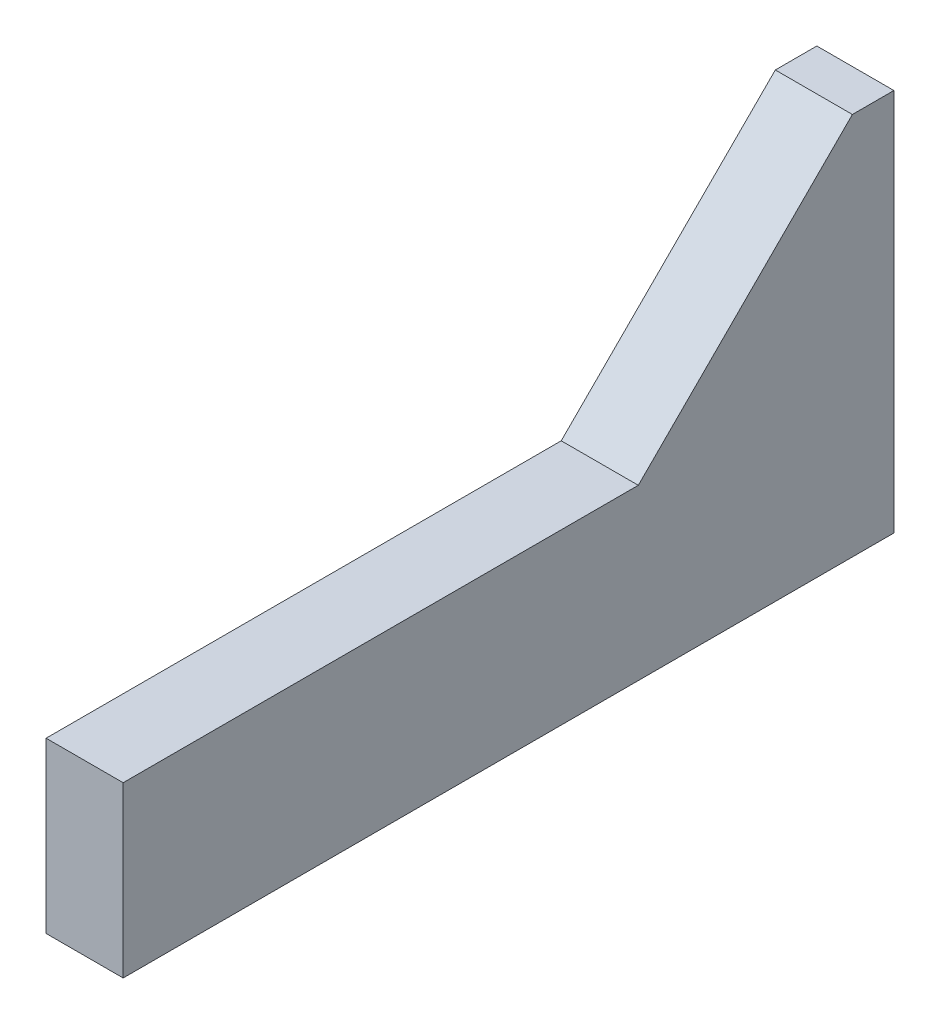
SolidWorks part; units mm, degrees
ref_plane "Спереди" through (0, 0, 0) normal (0, 0, 1) x (1, 0, 0)
ref_plane "Сверху" through (0, 0, 0) normal (0, 1, 0) x (1, 0, 0)
ref_plane "Справа" through (0, 0, 0) normal (1, 0, 0) x (0, 0, -1)
sketch "Эскиз1" plane through (0, 0, 0) normal (0, 0, 1) x (1, 0, 0)
  line L1 (-4.5, -7.5) -> (4.5, -7.5)
  line L2 (-4.5, -7.5) -> (-4.5, 7.5)
  line L3 (-4.5, 7.5) -> (4.5, 7.5)
  line L4 (4.5, -7.5) -> (4.5, 7.5)
  line L5 (-4.5, -7.5) -> (4.5, 7.5) construction
  line L6 (-4.5, 7.5) -> (4.5, -7.5) construction
  line L7 (-4.5, 7.5) -> (4.5, 7.5)
  line L8 (-4.5, 7.5) -> (-4.5, 12.25)
  line L9 (-4.5, 12.25) -> (4.5, 12.25)
  line L10 (4.5, 7.5) -> (4.5, 12.25)
  line L11 (4.5, 7.5) -> (-0.5, 7.5)
  line L12 (4.5, 7.5) -> (4.5, 9.75)
  line L13 (4.5, 9.75) -> (-0.5, 9.75)
  line L14 (-0.5, 7.5) -> (-0.5, 9.75)
  point P0 (0, 0)
  dimension "D1" = 9
  dimension "D2" = 15
  dimension "D3" = 2.25
  dimension "D4" = 2.5
  dimension "D5" = 4
extrude "Бобышка-Вытянуть1" add sketch "Эскиз1" along normal blind 90 contours L1 L4 L7 L3 L2 | L3 L14 L13 L10 L9 L8
sketch "Эскиз2" plane through (0, -7.5, 0) normal (0, -1, 0) x (1, 0, 0)
  line L0 (0, 90) -> (0, 67.5) construction
  line L1 (-4.5, 90) -> (4.5, 90) construction
  line L2 (0, 67.5) -> (0, 45) construction
  line L3 (0, 22.5) -> (0, 0) construction
  line L4 (-4.5, 0) -> (4.5, 0) construction
  line L5 (0, 45) -> (0, 22.5) construction
  circle A0 centre (0, 22.5) radius 2.1
  circle A1 centre (0, 67.5) radius 2.1
  circle A2 centre (0, 45) radius 2.1
  dimension "D1" = 4.2
extrude "Вырез-Вытянуть1" cut sketch "Эскиз2" against normal blind 6
sketch "Эскиз3" plane through (0, 0, 90) normal (0, 0, -1) x (-1, 0, 0)
  line L1 (-4.5, 9.75) -> (0.5, 9.75)
  line L2 (-4.5, 9.75) -> (-4.5, 7.5)
  line L3 (-4.5, 7.5) -> (0.5, 7.5)
  line L4 (0.5, 9.75) -> (0.5, 7.5)
extrude "Бобышка-Вытянуть2" add sketch "Эскиз3" along normal blind 3
chamfer "Фаска1" distance 0.75 angle 45 2 edges at (4.5, 7.5, 43.5) (4.5, 9.75, 43.5)
sketch "Эскиз5" plane through (-4.5, 0, 0) normal (-1, 0, 0) x (0, 0, 1)
  line L0 (0, 12.25) -> (0, 37.25)
  line L1 (0, 37.25) -> (4.8479, 37.25)
  line L2 (4.8479, 37.25) -> (29.8479, 12.25)
  line L3 (90, 12.25) -> (0, 12.25) construction
  line L4 (0, 12.25) -> (29.8479, 12.25)
  dimension "D1" = 45
  dimension "D2" = 25
extrude "Бобышка-Вытянуть3" add sketch "Эскиз5" against normal up to surface (9 mm away) contours L1 L2 L4 L0 up to face at (4.5, 5.5, 44.25)
sketch "Эскиз4" plane through (0, 0, 0) normal (0, 0, -1) x (-1, 0, 0)
  line L0 (-4.5, 37.25) -> (4.5, 37.25) construction
  line L1 (4.5, -7.5) -> (-4.5, -7.5) construction
  circle A0 centre (0, 2.5) radius 2.1
  circle A1 centre (0, 27.25) radius 2.1
  dimension "D1" = 4.2
  dimension "D2" = 10
  dimension "D3" = 10
extrude "Вырез-Вытянуть2" cut sketch "Эскиз4" against normal blind 6
mirror "Зеркальное отражение1" about plane through (-4.5, 0, 90) normal (-1, 0, 0) of bodies 104
delete or keep bodies "Тело-Удалить/Сохранить 1" type delete bodies bodies 104
